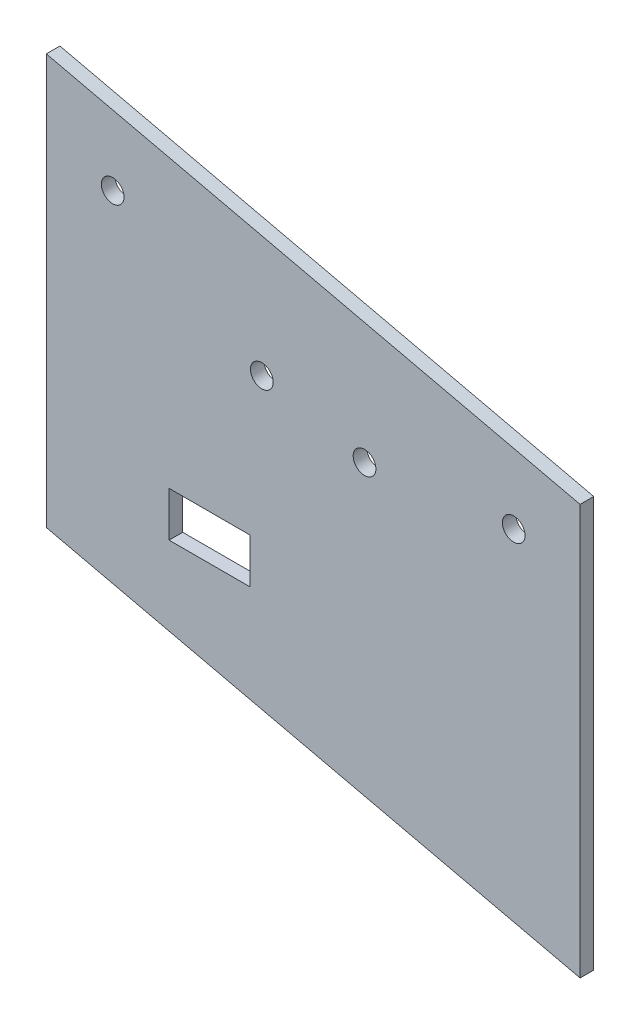
SolidWorks part; units mm, degrees
material "AISI 4340 Aço, normalizado"
ref_plane "Plano frontal" through (0, 0, 0) normal (0, 0, 1) x (1, 0, 0)
ref_plane "Plano superior" through (0, 0, 0) normal (0, 1, 0) x (1, 0, 0)
ref_plane "Plano direito" through (0, 0, 0) normal (1, 0, 0) x (0, 0, -1)
sketch "Esboço1" plane through (0, 0, 0) normal (0, 0, 1) x (1, 0, 0)
  line L0 (0, 0) -> (117.509, -27.1291)
  line L1 (117.509, -27.1291) -> (117.509, 63.1709)
  line L2 (117.509, 63.1709) -> (0, 90.3)
  line L3 (0, 90.3) -> (0, 0)
  dimension "D1" = 90.3
  dimension "D2" = 90.3
  dimension "D3" = 103
  dimension "D4" = 120.6
  dimension "D5" = 103
extrude "Ressalto-extrusão1" add sketch "Esboço1" along normal blind 3 contours L3 L0 L1 L2
hole_wizard "Broca de rosquear para tarraxa de M61" positions "Esboço2" profile "Esboço3" hole size "M6" standard "ISO" end condition through all
sketch "Esboço2" plane through (0, 0, 3) normal (0, 0, 1) x (1, 0, 0)
  line L0 (14.6156, 71.5312) -> (102.8935, 51.1506)
  line L1 (102.8935, 51.1506) -> (70.0572, 47.4421)
  line L2 (70.0572, 47.4421) -> (47.4518, 52.661)
  line L3 (47.4518, 52.661) -> (14.6156, 71.5312)
  line L5 (117.509, 63.1709) -> (0, 90.3) construction
  line L7 (102.8935, 51.1506) -> (117.509, 47.7763)
  line L8 (117.509, -27.1291) -> (117.509, 63.1709) construction
  line L10 (14.6156, 71.5312) -> (0, 74.9054)
  line L11 (0, 90.3) -> (0, 0) construction
  line L12 (47.4518, 52.661) -> (0, 63.6161)
  line L13 (70.0572, 47.4421) -> (117.509, 36.487)
  point P0 (14.6156, 71.5312)
  point P2 (102.8935, 51.1506)
  point P4 (70.0572, 47.4421)
  point P6 (47.4518, 52.661)
  dimension "D1" = 15
  dimension "D2" = 26
  dimension "D3" = 23.2
  dimension "D4" = 15
  dimension "D5" = 15
sketch "Esboço3" plane through (14.6156, 71.5312, 3) normal (1, 0, 0) x (0, -1, 0)
  line L0 (0, 0) -> (0, 3)
  line L1 (0, 3) -> (2.5, 3)
  line L2 (2.5, 3) -> (2.5, 0)
  line L5 (2.5, 0) -> (0, 0)
  line L11 (0, -6.35) -> (0, 107.95) construction
  dimension "Thru Hole Dia." = 5
  dimension "Thru Hole Depth" = 3
sketch "Esboço4" plane through (0, 0, 3) normal (0, 0, 1) x (1, 0, 0)
  line L1 (27.0302, 11.1103) -> (44.8347, 11.1103)
  line L2 (27.0302, 11.1103) -> (27.0302, 20.9837)
  line L3 (27.0302, 20.9837) -> (44.8347, 20.9837)
  line L4 (44.8347, 11.1103) -> (44.8347, 20.9837)
extrude "Corte-extrusão1" cut sketch "Esboço4" against normal through all
